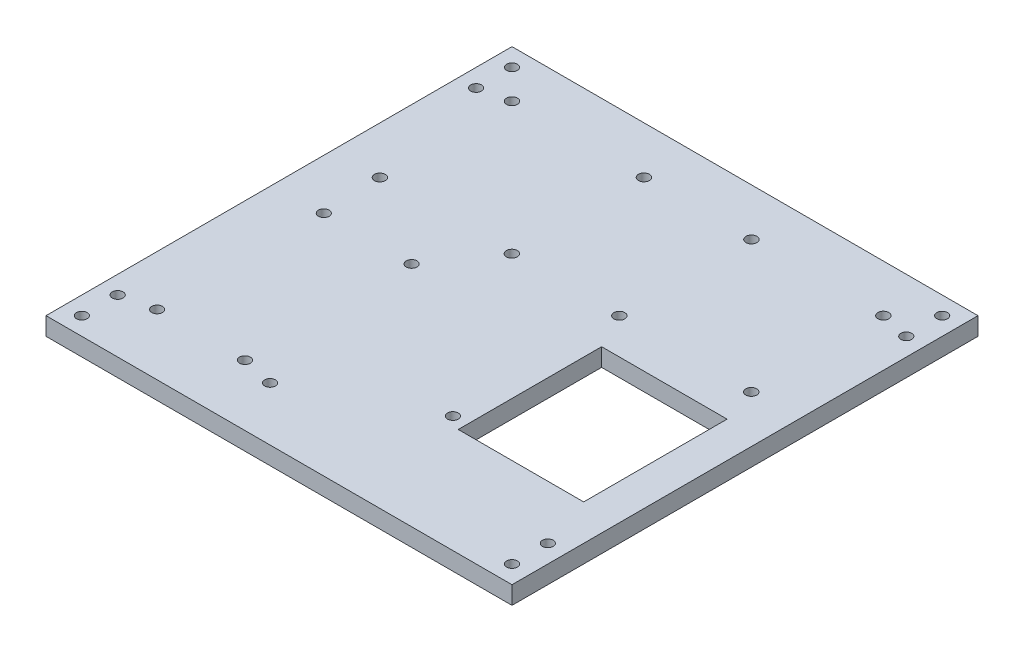
SolidWorks part; units mm, degrees
ref_plane "Front Plane" through (0, 0, 0) normal (0, 0, 1) x (1, 0, 0)
ref_plane "Top Plane" through (0, 0, 0) normal (0, 1, 0) x (1, 0, 0)
ref_plane "Right Plane" through (0, 0, 0) normal (1, 0, 0) x (0, 0, -1)
sketch "Sketch1" plane through (0, 0, 0) normal (0, 1, 0) x (1, 0, 0)
  line L1 (-65, 65) -> (65, 65)
  line L2 (-65, 65) -> (-65, -65)
  line L3 (-65, -65) -> (65, -65)
  line L4 (65, 65) -> (65, -65)
  line L5 (-65, 65) -> (65, -65) construction
  line L6 (-65, -65) -> (65, 65) construction
  point P0 (0, 0)
  dimension "D1" = 130
extrude "Boss-Extrude1" add sketch "Sketch1" along normal blind 5
sketch "Sketch4" plane through (0, 5, 0) normal (0, 1, 0) x (1, 0, 0)
  line L1 (65, 65) -> (-65, 65) construction
  line L3 (-65, 0) -> (65, 0) construction
  line L4 (-65, 65) -> (-65, -65) construction
  line L5 (65, -65) -> (65, 65) construction
  line L6 (0, 65) -> (0, -65) construction
  line L7 (-65, -65) -> (65, -65) construction
  circle A0 centre (60, 60) radius 1.5
  circle A1 centre (60, -60) radius 1.5
  circle A2 centre (-60, -60) radius 1.5
  circle A3 centre (-60, 60) radius 1.5
  dimension "D1" = 3
  dimension "D2" = 60
  dimension "D3" = 60
extrude "Cut-Extrude1" cut sketch "Sketch4" against normal up to surface (5 mm away) up to face at (0, 0, 0)
sketch "Sketch8" plane through (0, 5, 0) normal (0, 1, 0) x (1, 0, 0)
  circle A0 centre (-60, 50) radius 1.5
  circle A1 centre (60, 50) radius 1.5
  circle A2 centre (60, -50) radius 1.5
  circle A3 centre (-60, -50) radius 1.5
  dimension "D1" = 3
  dimension "D2" = 3
  dimension "D3" = 3
  dimension "D4" = 3
extrude "Cut-Extrude4" cut sketch "Sketch8" against normal up to surface (5 mm away) up to face at (-60, 0, -58.5)
sketch "Sketch9" plane through (0, 5, 0) normal (0, 1, 0) x (1, 0, 0)
  line L1 (20, 5) -> (55, 5)
  line L2 (20, 5) -> (20, -35)
  line L3 (20, -35) -> (55, -35)
  line L4 (55, 5) -> (55, -35)
  line L5 (20, 5) -> (55, -35) construction
  line L6 (20, -35) -> (55, 5) construction
  point P0 (37.5, -15)
  dimension "D1" = 40
  dimension "D2" = 35
  dimension "D3" = 55
  dimension "D4" = 35
extrude "Cut-Extrude5" cut sketch "Sketch9" against normal up to surface (5 mm away) up to face at (-60, 0, 51.5)
sketch "Sketch10" plane through (0, 5, 0) normal (0, 1, 0) x (1, 0, 0)
  circle A0 centre (-17.5, -50) radius 1.5
  dimension "D2" = 3
extrude "Cut-Extrude6" cut sketch "Sketch10" against normal up to surface (5 mm away) up to face at (37.5, 0, 15)
sketch "Sketch11" plane through (0, 5, 0) normal (0, 1, 0) x (1, 0, 0)
  circle A0 centre (-51.8037, 51.8) radius 1.525
  circle A1 centre (-14.9963, 51.8) radius 1.525
  circle A2 centre (14.9963, 51.8) radius 1.525
  circle A3 centre (51.8037, 51.8) radius 1.525
  circle A4 centre (51.8037, 14.95) radius 1.525
  circle A5 centre (14.9963, 14.95) radius 1.525
  circle A6 centre (-14.9963, 14.95) radius 1.525
  circle A7 centre (-51.8037, 14.95) radius 1.525
  circle A8 centre (-51, -1.5) radius 1.5
  circle A9 centre (-26.5, -1.5) radius 1.5
  circle A10 centre (-26.5, -48) radius 1.5
  circle A11 centre (-51, -48) radius 1.5
  dimension "D1" = 3
  dimension "D2" = 3.05
extrude "Cut-Extrude7" cut sketch "Sketch11" against normal up to surface (5 mm away) up to face at (-17.5, 0, 51.5)
sketch "Sketch12" plane through (0, 5, 0) normal (0, 1, 0) x (1, 0, 0)
  circle A0 centre (16, -32.5) radius 1.5
  dimension "D1" = 3
extrude "Cut-Extrude8" cut sketch "Sketch12" against normal up to surface (5 mm away) up to face at (-51, 0, 3)
